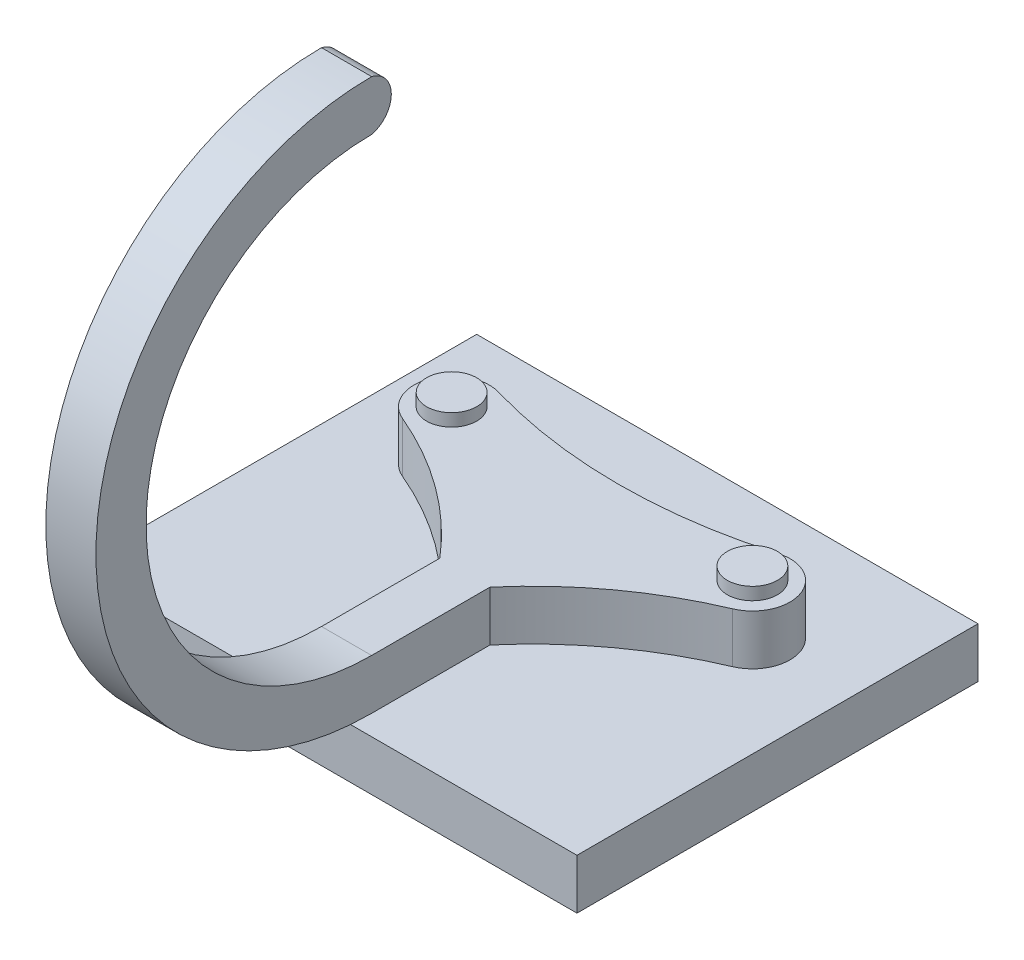
SolidWorks part; units mm, degrees
ref_plane "Front Plane" through (0, 0, 0) normal (0, 0, 1) x (1, 0, 0)
ref_plane "Top Plane" through (0, 0, 0) normal (0, 1, 0) x (1, 0, 0)
ref_plane "Right Plane" through (0, 0, 0) normal (1, 0, 0) x (0, 0, -1)
sketch "Sketch1" plane through (0, 0, 0) normal (0, 1, 0) x (1, 0, 0)
  line L1 (-10, 8) -> (10, 8)
  line L2 (-10, 8) -> (-10, -8)
  line L3 (-10, -8) -> (10, -8)
  line L4 (10, 8) -> (10, -8)
  line L5 (-10, 8) -> (10, -8) construction
  line L6 (-10, -8) -> (10, 8) construction
  point P0 (0, 0)
  dimension "D1" = 20
  dimension "D2" = 16
extrude "Boss-Extrude1" add sketch "Sketch1" along normal blind 2
sketch "Sketch2" plane through (0, 2, 0) normal (0, 1, 0) x (1, 0, 0)
  line L0 (10, 8) -> (-10, 8) construction
  line L1 (0, 0) -> (0, 15.1298) construction
  line L2 (0, 0) -> (0, -12.3745) construction
  line L3 (-1, -2.4698) -> (-1, -7.1909)
  line L5 (1, -2.4698) -> (1, -7.1909)
  line L7 (-1, -7.1909) -> (1, -7.1909)
  circle A0 centre (-6, 3) radius 1
  circle A1 centre (6, 3) radius 1
  arc A2 (-5.5814, 4.4404) -> (-6.5831, 1.618) centre (-6, 3) ccw
  arc A3 (6.5831, 1.618) -> (5.5814, 4.4404) centre (6, 3) ccw
  arc A4 (-6.5831, 1.618) -> (-1, -2.4698) centre (-12.4139, -12.2023) cw
  arc A5 (6.5831, 1.618) -> (1, -2.4698) centre (12.4139, -12.2023) ccw
  arc A6 (-5.5814, 4.4404) -> (5.5814, 4.4404) centre (0, 23.6458) ccw
  dimension "D3" = 2
  dimension "D6" = 3
  dimension "D7" = 3
  dimension "D10" = 20
  dimension "D11" = 15
  dimension "D1" = 5
  dimension "D2" = 5
  dimension "D4" = 6
  dimension "D5" = 6
  dimension "D8" = 1
  dimension "D9" = 1
extrude "Boss-Extrude2" add sketch "Sketch2" along normal blind 2
ref_plane "Plane1" through (0, 0, 0) normal (1, 0, 0) x (0, 0, -1)
sketch "Sketch8" plane through (0, 0, 0) normal (1, 0, 0) x (0, 0, -1)
  line L0 (-7.1909, 4) -> (-7.1909, 2)
  arc A0 (-7.1909, 4) -> (-7.1909, 22) centre (-7.1909, 13) cw
  arc A1 (-7.1909, 2) -> (-7.1909, 24) centre (-7.1909, 13) cw
  arc A2 (-7.1909, 24) -> (-7.1909, 22) centre (-7.4354, 23) cw
  dimension "D1" = 9
  dimension "D2" = 2
extrude "Boss-Extrude3" add sketch "Sketch8" along normal mid plane 2
sketch "Sketch10" plane through (0, 2, 0) normal (0, 1, 0) x (1, 0, 0)
  circle A0 centre (6, 3) radius 1 construction
  circle A1 centre (-6, 3) radius 1 construction
  circle A2 centre (6, 3) radius 1
  circle A3 centre (-6, 3) radius 1
extrude "Boss-Extrude4" add sketch "Sketch10" along normal blind 2.5
